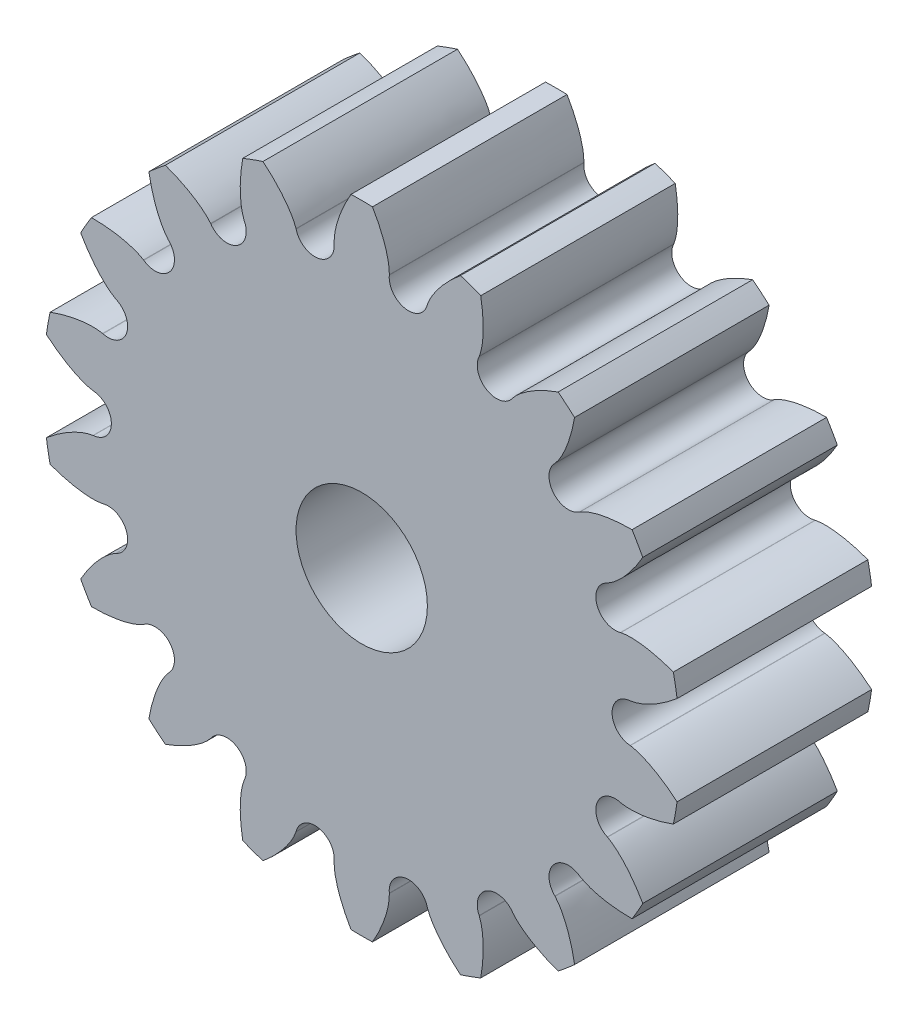
SolidWorks part; units mm, degrees
material "PE Low/Medium Density"
ref_plane "Front Plane" through (0, 0, 0) normal (0, 0, 1) x (1, 0, 0)
ref_plane "Top Plane" through (0, 0, 0) normal (0, 1, 0) x (1, 0, 0)
ref_plane "Right Plane" through (0, 0, 0) normal (1, 0, 0) x (0, 0, -1)
sketch "Involute construction sketch" plane through (0, 0, 0) normal (0, 0, 1) x (1, 0, 0)
  line L0 (0, 0) -> (-1.8, 3.7586) construction
  line L1 (0, 0) -> (-1.0856, 4.0235) construction
  line L2 (0, 0) -> (-0.3348, 4.1539) construction
  line L3 (0, 0) -> (0.4271, 4.1454) construction
  line L4 (-3.0265, 2.8648) -> (-2.4543, 3.368) construction
  line L5 (-2.4543, 3.368) -> (-1.8, 3.7586) construction
  line L6 (-1.8, 3.7586) -> (-1.0856, 4.0235) construction
  line L7 (0, 0) -> (-2.4543, 3.368) construction
  line L8 (0, 0) -> (-3.0265, 2.8648) construction
  line L9 (-1.0856, 4.0235) -> (-0.3348, 4.1539) construction
  line L10 (-0.3348, 4.1539) -> (0.4271, 4.1454) construction
  line L11 (-3.0265, 2.8648) -> (-0.4074, 5.6318) construction
  line L12 (-2.4543, 3.368) -> (0.009, 5.1631) construction
  line L13 (-1.8, 3.7586) -> (0.2617, 4.746) construction
  line L14 (-1.0856, 4.0235) -> (0.3858, 4.4205) construction
  line L15 (-0.3348, 4.1539) -> (0.4247, 4.2151) construction
  line L17 (0, 0) -> (0, 5.7859) construction
  line L18 (0, 0) -> (0.3865, 4.418) construction
  line L19 (0, 0) -> (0.6726, 3.8147) construction
  circle A0 centre (0, 0) radius 3.8735 construction
  circle A1 centre (0, 0) radius 4.1674 construction
  circle A2 centre (0, 0) radius 4.4348 construction
  circle A3 centre (0, 0) radius 4.9276 construction
  spline S0 degree 3 poles (0.4271, 4.1454) (0.4284, 4.2386) (0.3887, 4.4458) (0.1758, 4.9887) (-0.14, 5.3768) (-0.4074, 5.6318) knots 0 0 0 0 0.160044 0.360037 1 1 1 1 construction
  point P17 (0.1663, 4.9248)
  dimension "D1" = 7.747
  dimension "D2" = 8.3348
  dimension "D3" = 8.8697
  dimension "D4" = 9.8552
  dimension "D5" = 0.762
  dimension "D6" = 1.524
  dimension "D7" = 2.286
  dimension "D8" = 3.048
  dimension "D9" = 3.81
  dimension "D10" = 5
  dimension "D11" = 10
sketch "Sketch2" plane through (0, 0, 0) normal (0, 0, 1) x (1, 0, 0)
  line L0 (0, 4.9276) -> (0, 3.8735)
  line L1 (0, 0) -> (0, 5.7859) construction
  line L2 (0.4271, 4.1454) -> (0.4266, 4.1404)
  line L3 (0, 0) -> (0.4271, 4.1454) construction
  circle A0 centre (0, 0) radius 4.9276 construction
  circle A1 centre (0, 0) radius 3.8735 construction
  arc A2 (0, 4.9276) -> (0.1663, 4.9248) centre (0, 0) cw
  arc A3 (0, 3.8735) -> (0.6726, 3.8147) centre (0, 0) cw
  arc A4 (0.4266, 4.1404) -> (0.6726, 3.8147) centre (0.7247, 4.1097) ccw
  spline S0 degree 3 poles (0.1663, 4.9248) (0.2589, 4.7664) (0.3758, 4.5128) (0.4284, 4.2386) (0.4271, 4.1454) knots 0 0 0 0 0.664052 1 1 1 1
sketch "Sketch3" plane through (0, 0, 0) normal (0, 0, 1) x (1, 0, 0)
  circle A0 centre (0, 0) radius 3.8735
  circle A1 centre (0, 0) radius 1.016
  dimension "D1" = 7.747
  dimension "D2" = 2.032
extrude "Base" add sketch "Sketch3" along normal blind 3.0099
extrude "Half tooth" add sketch "Sketch2" along normal up to surface (3.0099 mm away) up to face at (3.8735, 0, 3.0099)
ref_plane "Midplane of half tooth" through (0, 0, 0) normal (-1, 0, 0) x (0, 0, 1)
mirror "Mirror of half tooth" about plane through (0, 0, 0) normal (-1, 0, 0) of "Half tooth"
pattern_circular "Pattern of tooth" count 18 over 360 of "Half tooth", "Mirror of half tooth"
equation "\"radtodeg\"= 180 / PI'radian to degree conversion [ ]"
equation "\"phi\"= 20'pressure angle [deg]"
equation "\"N\"= 18'number of teeth [teeth]"
equation "\"A\"= 0.388in'diameter of addendum circle [inch]"
equation "\"B\"= 0.305in'diameter of dedendum circle [inch]"
equation "\"P\"= ( \"N\" + 2 ) / \"A\"'diametral pitch [teeth/inch]"
equation "\"d\"= \"N\" / \"P\"'diameter of pitch circle [inch]"
equation "\"cp\"= PI / \"P\"'circular pitch [inch/teeth]"
equation "\"add\"= 1 / \"P\"'addendum [inch]"
equation "\"ded\"= - ( \"B\" - \"d\" ) / 2'dedendum [inch]"
equation "\"clear\"= \"ded\" - \"add\"'clearance [inch]"
equation "\"C\"= \"B\" + 2 * \"clear\"'diameter of clearance circle [inch]"
equation "\"h\"= \"add\" + \"ded\"'tooth height / whole depth [inch]"
equation "\"s\"= \"d\" * cos ( \"phi\" * 1 / \"radtodeg\" )'diameter of base circle [inch]"
equation "\"t\"= ( PI / 2 ) / \"P\"'tooth width at diameter of pitch circle diameter [inch]"
equation "\"alpha\"= ( \"t\" / ( \"d\" / 2 ) * \"radtodeg\" ) / 2'arc angle for half of tooth width at pitch circle diameter [inch]"
equation "\"bore\"= 0.0800'bore of hub [inch]"
equation "\"D4@Involute construction sketch\"= \"A\"'addendum circle"
equation "\"D3@Involute construction sketch\"= \"d\"'pitch circle"
equation "\"D2@Involute construction sketch\"= \"s\"'base circle"
equation "\"D1@Involute construction sketch\"= \"B\"'dedendum circle"
equation "\"seg\"= \"D5@Involute construction sketch\"'size of one involute segment [inch]"
equation "\"D6@Involute construction sketch\"=2*\"seg\""
equation "\"D7@Involute construction sketch\"=3*\"seg\""
equation "\"D8@Involute construction sketch\"=4*\"seg\""
equation "\"D9@Involute construction sketch\"=5*\"seg\""
equation "\"D10@Involute construction sketch\"=\"alpha\""
equation "\"D11@Involute construction sketch\"=2*\"alpha\""
equation "\"D1@Sketch3\"=\"B\""
equation "\"D1@CirPattern1\"=\"N\""
equation "\"D2@Sketch3\"=\"bore\""
